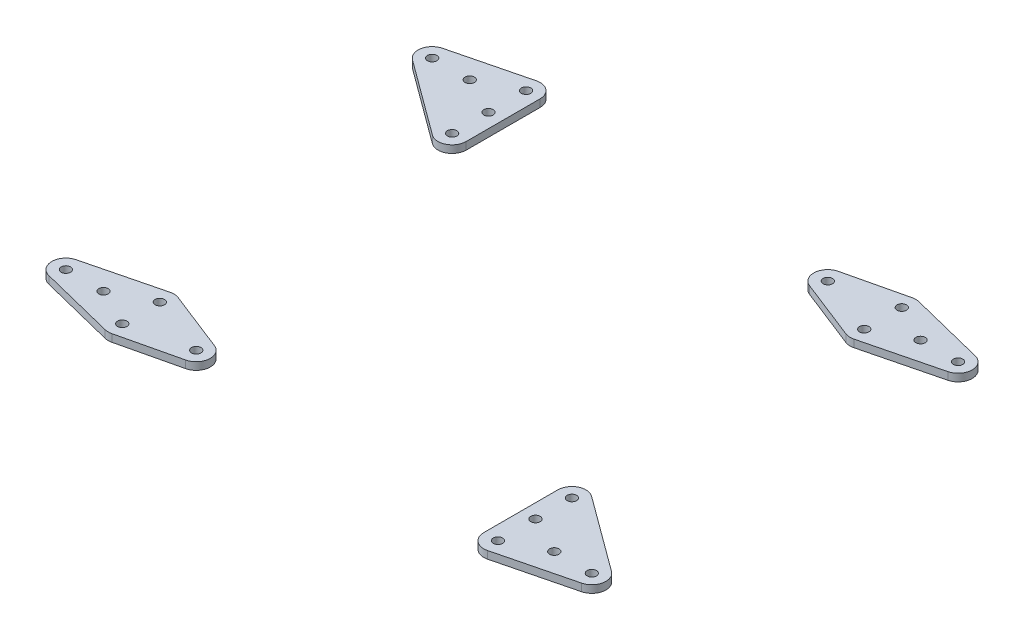
SolidWorks part; units mm, degrees
material "Thornel VCB-20 Carbon Cloth"
ref_plane "Front Plane" through (0, 0, 0) normal (0, 0, 1) x (1, 0, 0)
ref_plane "Top Plane" through (0, 0, 0) normal (0, 1, 0) x (1, 0, 0)
ref_plane "Right Plane" through (0, 0, 0) normal (1, 0, 0) x (0, 0, -1)
sketch "Sketch1" plane through (0, 0, 0) normal (0, 1, 0) x (1, 0, 0)
  line L0 (0, 165.4334) -> (0, -156.0403) construction
  line L1 (-197.6299, 0) -> (224.2115, 0) construction
  line L2 (-149.9096, 97.5) -> (-77.1705, 97.5) construction
  line L3 (-100, 114.9772) -> (-100, 25.6331) construction
  line L4 (-100, 68.1249) -> (0, 0) construction
  line L5 (-141.819, 104.7761) -> (-101.819, 114.7761)
  line L13 (-141.819, -90.2239) -> (-101.819, -80.2239)
  line L14 (-141.819, -104.7761) -> (-101.819, -114.7761)
  line L15 (141.819, -104.7761) -> (101.819, -114.7761)
  line L16 (141.819, 90.2239) -> (101.819, 80.2239)
  line L17 (141.819, 104.7761) -> (101.819, 114.7761)
  line L18 (92.5, -107.5) -> (92.5, -68.1249)
  line L19 (-92.5, 107.5) -> (-92.5, 68.1249)
  line L20 (-144.4393, 91.455) -> (-104.4393, 62.0799)
  line L21 (-97.2619, -80.5177) -> (-65.3867, -93.0177)
  line L22 (-68.1249, -100) -> (0, 0) construction
  line L23 (-98.2822, -114.8006) -> (-66.4071, -107.3006)
  line L24 (144.4393, -91.455) -> (104.4393, -62.0799)
  line L25 (97.2619, 80.5177) -> (65.3867, 93.0177)
  line L26 (98.2822, 114.8006) -> (66.4071, 107.3006)
  line L27 (149.9096, -97.5) -> (77.1705, -97.5) construction
  line L28 (100, -114.9772) -> (100, -25.6331) construction
  circle A0 centre (-140, 97.5) radius 2.5
  circle A1 centre (-120, 97.5) radius 2.5
  circle A2 centre (-100, 107.5) radius 2.5
  circle A3 centre (-100, 87.5) radius 2.5
  circle A4 centre (0, 0) radius 121 construction
  arc A6 (-141.819, 104.7761) -> (-144.4393, 91.455) centre (-140, 97.5) ccw
  arc A7 (-92.5, 107.5) -> (-101.819, 114.7761) centre (-100, 107.5) ccw
  circle A11 centre (-140, 97.5) radius 7.5 construction
  arc A12 (-104.4393, 62.0799) -> (-92.5, 68.1249) centre (-100, 68.1249) ccw
  circle A13 centre (-100, 68.1249) radius 2.5
  circle A14 centre (-100, 107.5) radius 7.5 construction
  circle A20 centre (-68.1249, -100) radius 2.5
  arc A21 (-97.2619, -80.5177) -> (-101.819, -80.2239) centre (-100, -87.5) ccw
  arc A22 (-98.2822, -114.8006) -> (-101.819, -114.7761) centre (-100, -107.5) cw
  arc A23 (-141.819, -104.7761) -> (-141.819, -90.2239) centre (-140, -97.5) cw
  circle A24 centre (-100, -87.5) radius 2.5
  circle A25 centre (-100, -107.5) radius 2.5
  circle A26 centre (-120, -97.5) radius 2.5
  circle A27 centre (-140, -97.5) radius 2.5
  circle A32 centre (140, -97.5) radius 2.5
  circle A33 centre (120, -97.5) radius 2.5
  circle A34 centre (100, -107.5) radius 2.5
  circle A35 centre (100, -87.5) radius 2.5
  arc A36 (141.819, -104.7761) -> (144.4393, -91.455) centre (140, -97.5) ccw
  arc A37 (92.5, -107.5) -> (101.819, -114.7761) centre (100, -107.5) ccw
  arc A42 (-66.4071, -107.3006) -> (-65.3867, -93.0177) centre (-68.1249, -100) ccw
  circle A43 centre (-100, 68.1249) radius 7.5 construction
  arc A44 (104.4393, -62.0799) -> (92.5, -68.1249) centre (100, -68.1249) ccw
  circle A45 centre (-68.1249, -100) radius 7.5 construction
  circle A46 centre (100, -68.1249) radius 2.5 [skipped]
  circle A47 centre (68.1249, 100) radius 2.5 [skipped]
  circle A48 centre (100, -68.1249) radius 2.5
  circle A49 centre (68.1249, 100) radius 2.5
  arc A50 (97.2619, 80.5177) -> (101.819, 80.2239) centre (100, 87.5) ccw
  arc A51 (98.2822, 114.8006) -> (101.819, 114.7761) centre (100, 107.5) cw
  arc A52 (141.819, 104.7761) -> (141.819, 90.2239) centre (140, 97.5) cw
  circle A53 centre (100, 87.5) radius 2.5
  circle A54 centre (100, 107.5) radius 2.5
  circle A55 centre (120, 97.5) radius 2.5
  circle A56 centre (140, 97.5) radius 2.5
  arc A57 (66.4071, 107.3006) -> (65.3867, 93.0177) centre (68.1249, 100) ccw
  point P26 (-100, 87.5)
  point P27 (-78.0599, 85.5599)
  point P28 (-85.5599, 85.5599)
  point P29 (-102.5, 107.5)
  point P36 (-132.5, 97.5)
  point P38 (-102.5, 87.5)
  point P40 (-92.5, 68.1249)
  point P47 (0, 0)
  point P95 (-60.6249, -100)
  point P114 (0, 0)
  dimension "D1" = 5
  dimension "D2" = 5
  dimension "D3" = 5
  dimension "D9" = 242
  dimension "D11" = 4
  dimension "D17" = 2
  dimension "D10" = 5
  dimension "D15" = 7.5
  dimension "D16" = 90
  dimension "D4" = 10
  dimension "D5" = 20
  dimension "D6" = 20
  dimension "D7" = 140
  dimension "D8" = 107.5
  dimension "D13" = 5
  dimension "D14" = 5
  dimension "D12" = 5
extrude "Boss-Extrude1" add sketch "Sketch1" along normal blind 4
